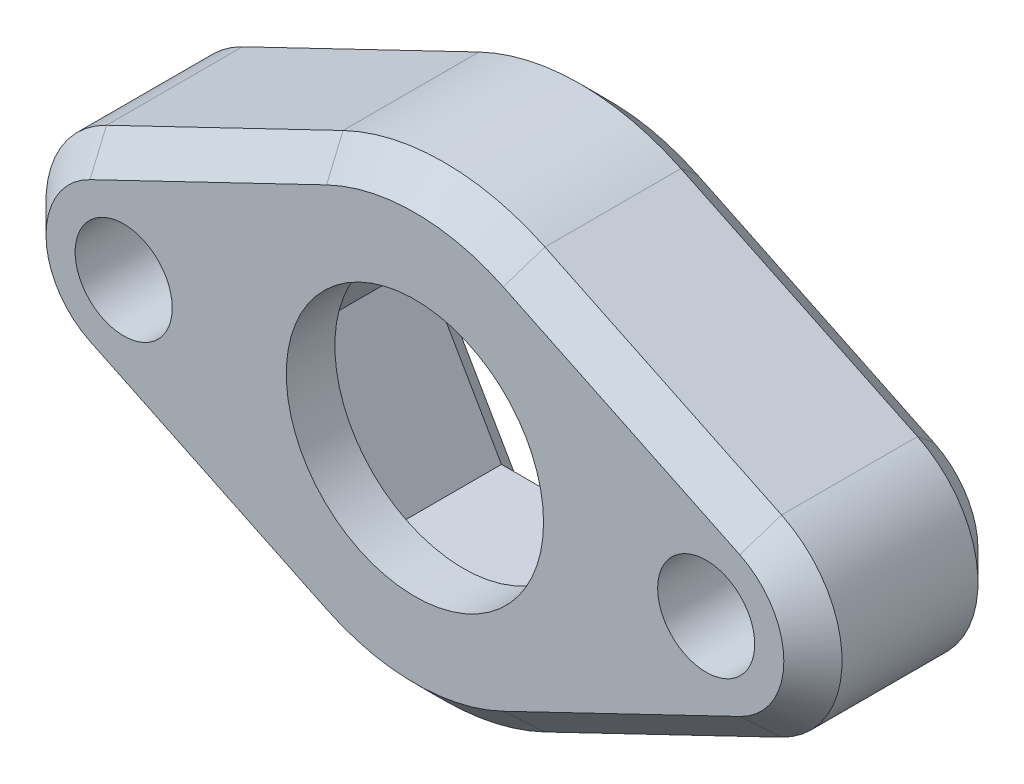
SolidWorks part; units mm, degrees
ref_plane "Front Plane" through (0, 0, 0) normal (0, 0, 1) x (1, 0, 0)
ref_plane "Top Plane" through (0, 0, 0) normal (0, 1, 0) x (1, 0, 0)
ref_plane "Right Plane" through (0, 0, 0) normal (1, 0, 0) x (0, 0, -1)
sketch "Sketch1" plane through (0, 0, 0) normal (0, 0, 1) x (1, 0, 0)
  line L0 (-5.2, -10.8148) -> (-17.3833, -4.9568)
  line L1 (-5.2, 10.8148) -> (-17.3833, 4.9568)
  line L2 (0, 12) -> (0, -12) construction
  line L3 (8.0829, 0) -> (4.0415, 7)
  line L4 (4.0415, 7) -> (-4.0415, 7)
  line L5 (-4.0415, 7) -> (-8.0829, 0)
  line L6 (-8.0829, 0) -> (-4.0415, -7)
  line L7 (-4.0415, -7) -> (4.0415, -7)
  line L8 (4.0415, -7) -> (8.0829, 0)
  line L9 (5.2, 10.8148) -> (17.3833, 4.9568)
  line L10 (5.2, -10.8148) -> (17.3833, -4.9568)
  arc A0 (-5.2, -10.8148) -> (5.2, -10.8148) centre (0, 0) ccw
  arc A1 (-17.3833, -4.9568) -> (-17.3833, 4.9568) centre (-15, 0) cw
  circle A2 centre (-15, 0) radius 2.5
  circle A3 centre (0, 0) radius 7 construction
  arc A4 (17.3833, -4.9568) -> (17.3833, 4.9568) centre (15, 0) ccw
  circle A5 centre (15, 0) radius 2.5
  arc A6 (5.2, 10.8148) -> (-5.2, 10.8148) centre (0, 0) ccw
  dimension "D1" = 24
  dimension "D2" = 5
  dimension "D4" = 3
  dimension "D3" = 15
  dimension "D5" = 14
extrude "Boss-Extrude1" add sketch "Sketch1" along normal blind 10
sketch "Sketch2" plane through (0, 0, 10) normal (0, 0, 1) x (1, 0, 0)
  circle A0 centre (0, 0) radius 8.0829
  circle A1 centre (0, 0) radius 6.625
  dimension "D1" = 13.25
extrude "Boss-Extrude3" add sketch "Sketch2" against normal blind 2.5
chamfer "Chamfer1" distance 1.5 angle 45 22 edges at (20.5, 0, 10) (11.2917, 7.8858, 10) (11.2917, -7.8858, 10) (0, 12, 10) (0, -12, 10) (-11.2917, 7.8858, 10) (-11.2917, -7.8858, 10) (-20.5, 0, 10) (6.0622, 3.5, 0) (6.0622, -3.5, 0) (0, -7, 0) (-6.0622, -3.5, 0) (-6.0622, 3.5, 0) (0, 7, 0) (0, 12, 0) (-11.2917, 7.8858, 0) (11.2917, 7.8858, 0) (-20.5, 0, 0) (20.5, 0, 0) (-11.2917, -7.8858, 0) (11.2917, -7.8858, 0) (0, -12, 0)
